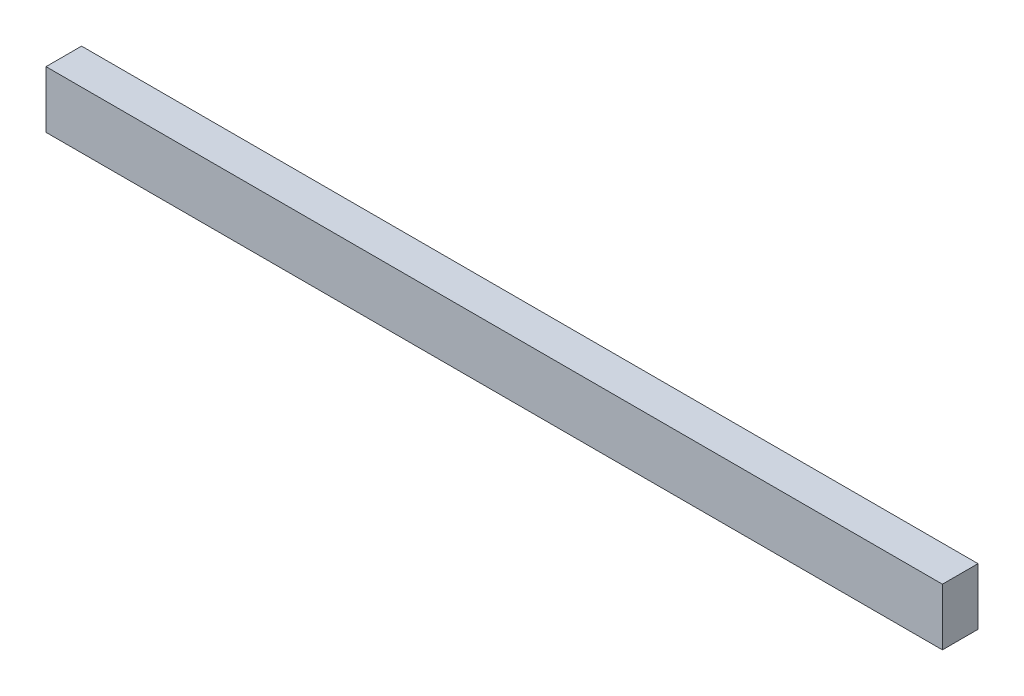
SolidWorks part; units mm, degrees
ref_plane "Front Plane" through (0, 0, 0) normal (0, 0, 1) x (1, 0, 0)
ref_plane "Top Plane" through (0, 0, 0) normal (0, 1, 0) x (1, 0, 0)
ref_plane "Right Plane" through (0, 0, 0) normal (1, 0, 0) x (0, 0, -1)
other "Configuration Table"
sketch "Sketch1" plane through (0, 0, 0) normal (0, 0, 1) x (1, 0, 0)
  line L1 (700, 1620) -> (1330, 1620)
  line L2 (700, 1620) -> (700, 1660)
  line L3 (700, 1660) -> (1330, 1660)
  line L4 (1330, 1620) -> (1330, 1660)
extrude "STORE_kablo_kanali_yatay_40x25_1" add sketch "Sketch1" against normal blind 25 from offset 727 separate body
